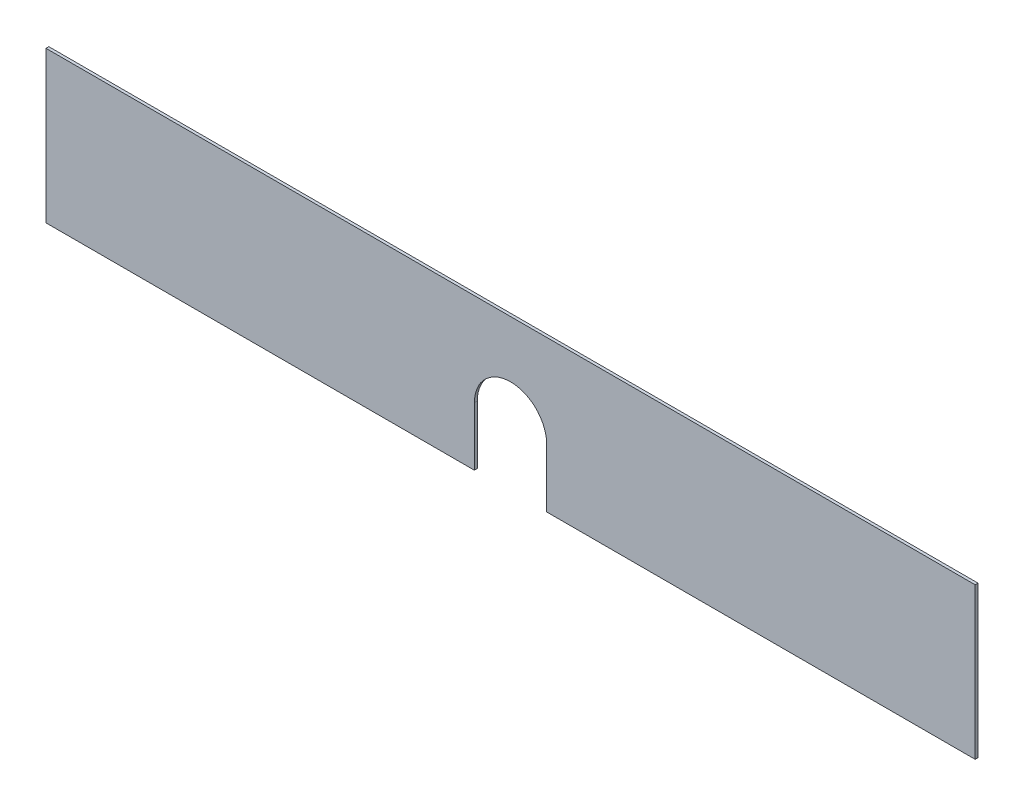
SolidWorks part; units mm, degrees
ref_plane "Front Plane" through (0, 0, 0) normal (0, 0, 1) x (1, 0, 0)
ref_plane "Top Plane" through (0, 0, 0) normal (0, 1, 0) x (1, 0, 0)
ref_plane "Right Plane" through (0, 0, 0) normal (1, 0, 0) x (0, 0, -1)
sketch "Sketch1" plane through (0, 0, 0) normal (0, 0, 1) x (1, 0, 0)
  line L0 (0, 0) -> (0, 53)
  line L1 (0, 53) -> (325.71, 53)
  line L2 (325.71, 53) -> (325.71, 0)
  line L3 (325.71, 0) -> (175.535, 0)
  line L6 (150.175, 20.5) -> (150.175, 0)
  line L7 (175.535, 20.5) -> (175.535, 0)
  line L8 (150.175, 0) -> (0, 0)
  arc A0 (150.175, 20.5) -> (175.535, 20.5) centre (162.855, 20.5) cw
  dimension "D1" = 53
  dimension "D2" = 325.71
extrude "Boss-Extrude1" add sketch "Sketch1" along normal blind 1
